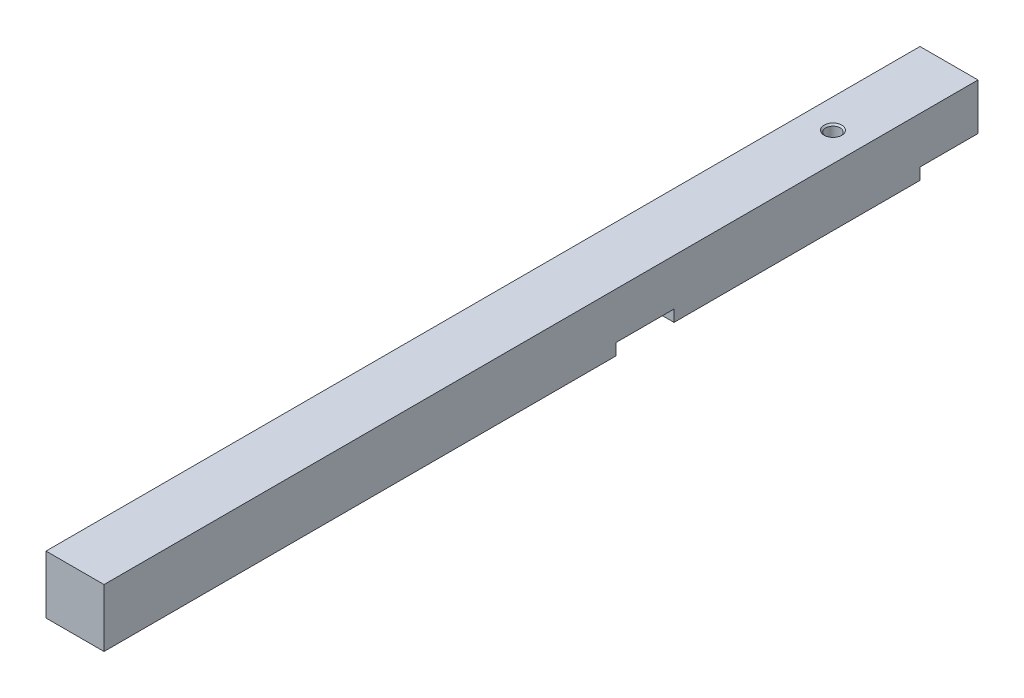
SolidWorks part; units mm, degrees
ref_plane "Plan de face" through (0, 0, 0) normal (0, 0, 1) x (1, 0, 0)
ref_plane "Plan de dessus" through (0, 0, 0) normal (0, 1, 0) x (1, 0, 0)
ref_plane "Plan de droite" through (0, 0, 0) normal (1, 0, 0) x (0, 0, -1)
sketch "Esquisse1" plane through (0, 0, 0) normal (0, 0, 1) x (1, 0, 0)
  line L0 (-5, 5) -> (5, -5) construction
  line L1 (-5, 5) -> (5, 5)
  line L2 (-5, 5) -> (-5, -5)
  line L3 (-5, -5) -> (5, -5)
  line L4 (5, 5) -> (5, -5)
  dimension "D1" = 10
extrude "Boss.-Extru.1" add sketch "Esquisse1" along normal up to surface (150.6649 mm away)
sketch "Esquisse2" plane through (-5, 0, 0) normal (-1, 0, 0) x (0, 0, 1)
  line L0 (0, -3) -> (0, -303) construction
  line L1 (0, -5) -> (10, -5)
  line L2 (0, -5) -> (0, -3)
  line L3 (0, -3) -> (10, -3)
  line L4 (10, -5) -> (10, -3)
  line L5 (10, -3) -> (10, -170) construction
  line L6 (52.4, -3) -> (52.4, -170) construction
  line L7 (52.4, -5) -> (62.4, -5)
  line L8 (52.4, -5) -> (52.4, -3)
  line L9 (52.4, -3) -> (62.4, -3)
  line L10 (62.4, -5) -> (62.4, -3)
  line L11 (62.4, -3) -> (62.4, -170) construction
  line L18 (150.6649, -5) -> (0, -5) construction
  dimension "D1" = 2
extrude "Enlèv. mat.-Extru.1" cut sketch "Esquisse2" against normal through all
sketch "Esquisse3" plane through (0, -5, 0) normal (0, -1, 0) x (1, 0, 0)
  line L4 (3, 36.2) -> (3, 26.2)
  line L5 (234, 36.2) -> (3, 36.2)
  line L6 (234, 26.2) -> (234, 36.2)
  line L7 (3, 26.2) -> (234, 26.2)
  line L8 (3, 36.2) -> (3, 26.2)
  line L9 (234, 36.2) -> (3, 36.2)
  line L10 (234, 26.2) -> (234, 36.2)
  line L11 (3, 26.2) -> (234, 26.2)
  dimension "D1" = 0
extrude "Enlèv. mat.-Extru.2" [suppressed] cut sketch "Esquisse3" against normal through all
hole_wizard "Trou taraudé M3x0.51" positions "Esquisse7" profile "Esquisse6" tap size "M3x0.5" standard "Ansi Metric" end condition through all
sketch "Esquisse7" plane through (0, 5, 0) normal (0, 1, 0) x (1, 0, 0)
  point P0 (0, -20)
sketch "Esquisse6" plane through (0, 5, 20) normal (1, 0, 0) x (0, 0, 1)
  line L0 (0, 0) -> (0, 10)
  line L1 (0, 10) -> (1.25, 10)
  line L2 (1.25, 10) -> (1.25, 0.275)
  line L3 (1.25, 0.275) -> (1.525, 0)
  line L5 (1.525, 0) -> (0, 0)
  line L6 (-1.25, 0.275) -> (-1.525, 0) construction
  line L11 (0, -6.35) -> (0, 107.95) construction
  dimension "Diamètre du trou pour taraudage jusqu'au prochain" = 2.5
  dimension "Profondeur du trou pour taraudage jusqu'au prochain" = 10
  dimension "Diamètre du fraisage entrant" = 3.05
  dimension "Angle du fraisage entrant" = 90
cosmetic thread "Filetage de perçage2" parameters "D2"=3
